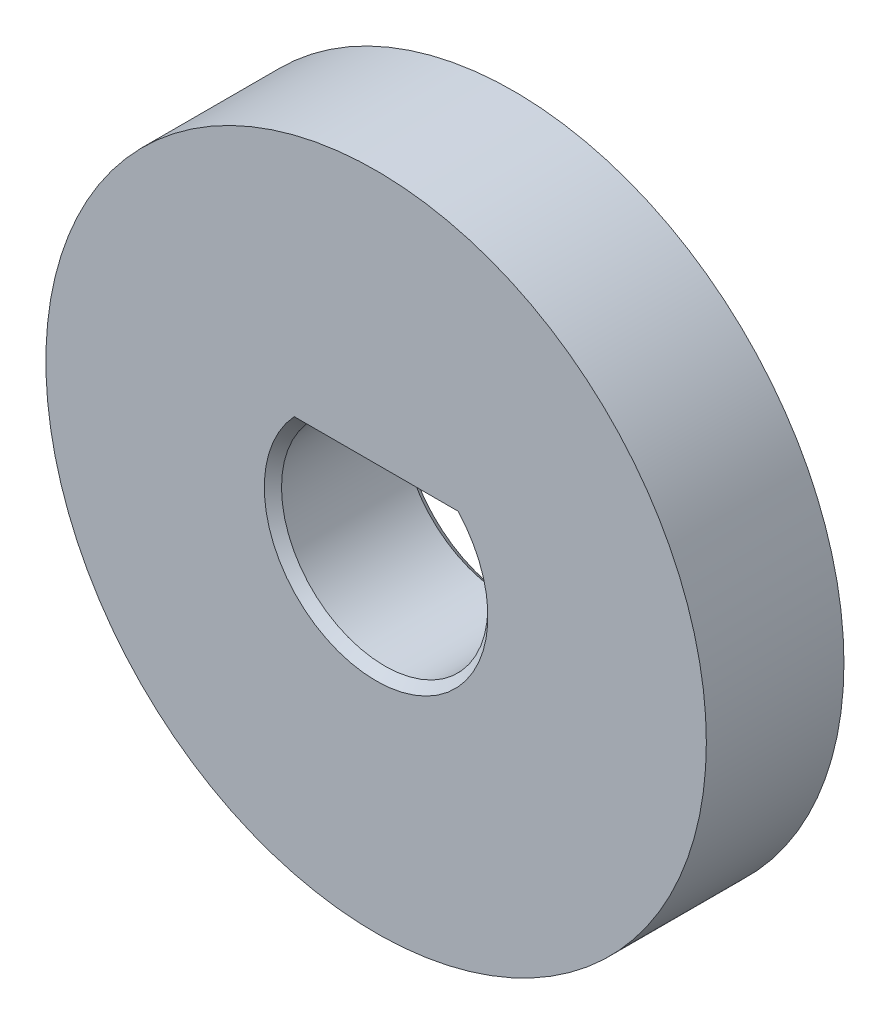
SolidWorks part; units mm, degrees
material "6061-T6 (SS)"
ref_plane "Front Plane" through (0, 0, 0) normal (0, 0, 1) x (1, 0, 0)
ref_plane "Top Plane" through (0, 0, 0) normal (0, 1, 0) x (1, 0, 0)
ref_plane "Right Plane" through (0, 0, 0) normal (1, 0, 0) x (0, 0, -1)
sketch "Sketch1" plane through (0, 0, 0) normal (0, 0, 1) x (1, 0, 0)
  circle A0 centre (0, 0) radius 30.48
  circle A1 centre (0, 0) radius 9.525
  dimension "D1" = 60.96
  dimension "D2" = 19.05
extrude "Extrude1" add sketch "Sketch1" along normal mid plane 12.7
sketch "Sketch2" plane through (0, 0, 0) normal (1, 0, 0) x (0, 0, -1)
  line L0 (-4.7625, 19.05) -> (4.7625, 19.05)
  line L2 (4.7625, 19.05) -> (2.4513, 12.7)
  line L3 (2.4513, 12.7) -> (-2.4513, 12.7)
  line L4 (-2.4513, 12.7) -> (-4.7625, 19.05)
  line L5 (-6.35, 0) -> (6.35, 0) construction
  line L6 (-6.35, 30.48) -> (-6.35, -30.48) construction
  line L7 (6.35, -30.48) -> (6.35, 30.48) construction
  point P2 (0, 19.05)
  point P5 (0, 12.7)
  dimension "D1" = 19.05
  dimension "D2" = 6.35
  dimension "D3" = 9.525
  dimension "D4" = 40
chamfer "Chamfer1" distance 0.7937 angle 45 2 edges at (9.525, 0, -6.35) (9.525, 0, 6.35)
sketch "Sketch3" plane through (0, 0, -6.35) normal (0, 0, -1) x (-1, 0, 0)
  line L0 (0, 0) -> (0, 9.525) construction
  line L5 (-7.5582, 7.025) -> (7.5582, 7.025)
  circle A1 centre (0, 0) radius 10.3188 construction
  circle A2 centre (0, 0) radius 9.525 construction
  arc A3 (-7.5582, 7.025) -> (7.5582, 7.025) centre (0, 0) cw
  dimension "D1" = 2.5
extrude "Boss-Extrude1" add sketch "Sketch3" against normal through all
